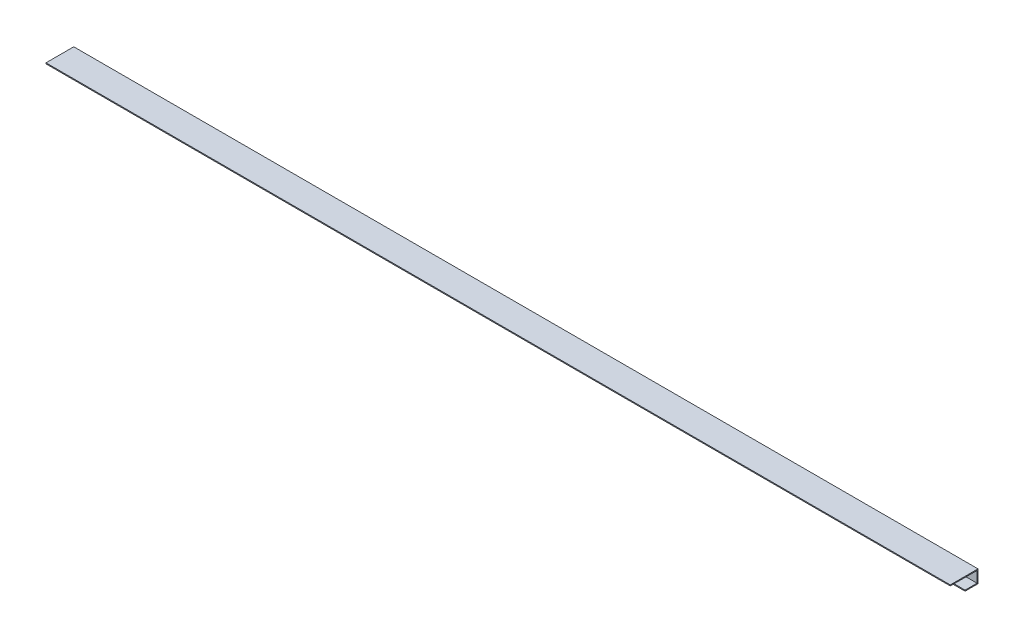
SolidWorks part; units mm, degrees
ref_plane "Front Plane" through (0, 0, 0) normal (0, 0, 1) x (1, 0, 0)
ref_plane "Top Plane" through (0, 0, 0) normal (0, 1, 0) x (1, 0, 0)
ref_plane "Right Plane" through (0, 0, 0) normal (1, 0, 0) x (0, 0, -1)
sketch "Sketch1" plane through (0, 0, 0) normal (1, 0, 0) x (0, 0, -1)
  line L0 (0, 0) -> (58, 0)
  line L1 (58, 0) -> (58, -27)
  line L2 (58, -27) -> (31, -27)
  line L3 (0, -2) -> (56, -2)
  line L4 (56, -2) -> (56, -25)
  line L5 (56, -25) -> (31, -25)
  line L6 (0, 0) -> (0, -2)
  line L7 (31, -25) -> (31, -27)
  dimension "D1" = 2
  dimension "D2" = 58
  dimension "D3" = 27
  dimension "D4" = 27
extrude "Boss-Extrude1" add sketch "Sketch1" along normal blind 1890
equation "\"door_base_short7_R1_R_open_Single_height\"=1890.0"
equation "\"D1@Boss-Extrude1\"=\"door_base_short7_R1_R_open_Single_height\""
equation "\"CarBeamWidth\"=700.0"
equation "\"WheelWidth\"=650.0"
equation "\"Wheel_FrontBoxDistance\"=1390.0"
equation "\"MetalSheet_3mm_length\"=5030.0"
equation "\"MetalSheet_3mm_width\"=1923.0"
equation "\"MetalSheet_3mm_FloorCut_L_length\"=1764.0"
equation "\"MetalSheet_3mm_FloorCut_L_disdance\"=1665.0"
equation "\"MetalSheet_3mm_FloorCut_R_length\"=1764.0"
equation "\"MetalSheet_3mm_FloorCut_R_disdance\"=1665.0"
equation "\"indoorHeight\"=1940.0"
equation "\"haveDoor_R\"=1"
equation "\"side_door_bottom_R_3mm_length\"=1934.0"
equation "\"1Bar_Side_RF_3mm_length\"=1493.0"
equation "\"1Bar_Side_RB_3mm_length\"=1493.0"
equation "\"DoorSeparator_RF_3mm_withHinge_toFrontDistance\"=1673.0"
equation "\"DoorSeparator_RF_3mm_withHinge_exist\"=1"
equation "\"DoorSeparator_RB_3mm_withHinge_toFrontDistance\"=3427.0"
equation "\"DoorSeparator_RB_3mm_withHinge_exist\"=1"
equation "\"Door_R1_L_open_Single_toFrontDistance\"=2547.5"
equation "\"Door_R1_L_open_Single_exist\"=1"
equation "\"door_base_long7_R1_L_open_Single_height\"=1890.0"
equation "\"door_base_short7_R1_L_open_Single_height\"=1890.0"
equation "\"door_base_short7_R1_L_open_Single_width\"=864"
equation "\"Door_R1_R_open_Single_toFrontDistance\"=3422.0"
equation "\"Door_R1_R_open_Single_exist\"=1"
equation "\"door_base_long7_R1_R_open_Single_height\"=1890.0"
equation "\"door_base_short7_R1_R_open_Single_width\"=864"
equation "\"x\"=66.0"
equation "\"da\"=62.0"
equation "\"SquareTube_length\"=1923.0"
equation "\"channelSteel_length\"=5030.0"
equation "\"SquareTube_inFront_AvgDistance\"=285.0"
equation "\"SquareTube_inFront_TotalCount\"=5"
equation "\"SquareTube_inFront1_cutDepth50_R\"=0.5"
equation "\"SquareTube_inFront1_cutDepth50_L\"=0.5"
equation "\"SquareTube_inFront2_cutDepth50_R\"=0.5"
equation "\"SquareTube_inFront2_cutDepth50_L\"=0.5"
equation "\"SquareTube_inFront3_cutDepth50_R\"=0.5"
equation "\"SquareTube_inFront3_cutDepth50_L\"=0.5"
equation "\"SquareTube_inFront4_cutDepth50_R\"=0.5"
equation "\"SquareTube_inFront4_cutDepth50_L\"=0.5"
equation "\"SquareTube_inFront5_cutDepth50_R\"=50"
equation "\"SquareTube_inFront5_cutDepth50_L\"=50"
equation "\"SquareTube_inFront6_cutDepth50_R\"=50"
equation "\"SquareTube_inFront6_cutDepth50_L\"=50"
equation "\"SquareTube_inFront7_cutDepth50_R\"=50"
equation "\"SquareTube_inFront7_cutDepth50_L\"=50"
equation "\"SquareTube_inFront8_cutDepth50_R\"=50"
equation "\"SquareTube_inFront8_cutDepth50_L\"=50"
equation "\"SquareTube_inFront9_cutDepth50_R\"=50"
equation "\"SquareTube_inFront9_cutDepth50_L\"=50"
equation "\"SquareTube_inFront10_cutDepth50_R\"=50"
equation "\"SquareTube_inFront10_cutDepth50_L\"=50"
equation "\"SquareTube_inFront11_cutDepth50_R\"=50"
equation "\"SquareTube_inFront11_cutDepth50_L\"=50"
equation "\"SquareTube_inFront12_cutDepth50_R\"=50"
equation "\"SquareTube_inFront12_cutDepth50_L\"=50"
equation "\"SquareTube_inFront13_cutDepth50_R\"=50"
equation "\"SquareTube_inFront13_cutDepth50_L\"=50"
equation "\"SquareTube_inFront14_cutDepth50_R\"=50"
equation "\"SquareTube_inFront14_cutDepth50_L\"=50"
equation "\"SquareTube_inBack_AvgDistance\"=333.125"
equation "\"SquareTube_inBack_TotalCount\"=9"
equation "\"SquareTube_inBack1_cutDepth50_R\"=50"
equation "\"SquareTube_inBack1_cutDepth50_L\"=50"
equation "\"SquareTube_inBack2_cutDepth50_R\"=50"
equation "\"SquareTube_inBack2_cutDepth50_L\"=50"
equation "\"SquareTube_inBack3_cutDepth50_R\"=50"
equation "\"SquareTube_inBack3_cutDepth50_L\"=50"
equation "\"SquareTube_inBack4_cutDepth50_R\"=50"
equation "\"SquareTube_inBack4_cutDepth50_L\"=50"
equation "\"SquareTube_inBack5_cutDepth50_R\"=50"
equation "\"SquareTube_inBack5_cutDepth50_L\"=50"
equation "\"SquareTube_inBack6_cutDepth50_R\"=0.5"
equation "\"SquareTube_inBack6_cutDepth50_L\"=0.5"
equation "\"SquareTube_inBack7_cutDepth50_R\"=0.5"
equation "\"SquareTube_inBack7_cutDepth50_L\"=0.5"
equation "\"SquareTube_inBack8_cutDepth50_R\"=0.5"
equation "\"SquareTube_inBack8_cutDepth50_L\"=0.5"
